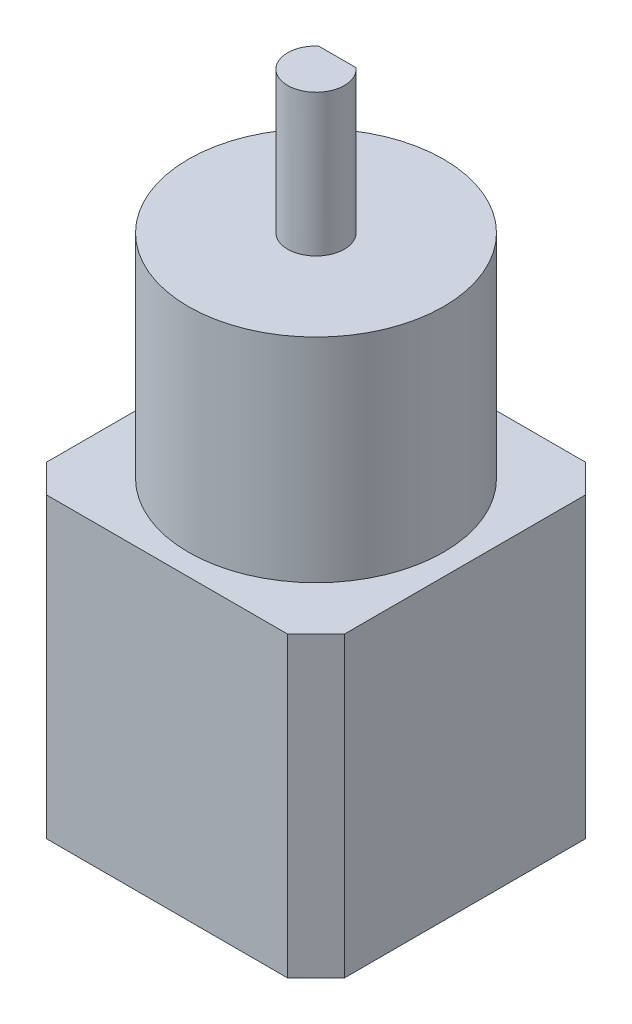
SolidWorks part; units mm, degrees
ref_plane "정면" through (0, 0, 0) normal (0, 0, 1) x (1, 0, 0)
ref_plane "윗면" through (0, 0, 0) normal (0, 1, 0) x (1, 0, 0)
ref_plane "우측면" through (0, 0, 0) normal (1, 0, 0) x (0, 0, -1)
sketch "스케치1" plane through (0, 0, 0) normal (0, 1, 0) x (1, 0, 0)
  line L1 (-21, -21) -> (21, -21)
  line L2 (-21, -21) -> (-21, 21)
  line L3 (-21, 21) -> (21, 21)
  line L4 (21, -21) -> (21, 21)
  line L5 (-21, -21) -> (21, 21) construction
  line L6 (-21, 21) -> (21, -21) construction
  point P0 (0, 0)
  dimension "D1" = 42
  dimension "D2" = 42
extrude "보스-돌출1" add sketch "스케치1" along normal mid plane 42
chamfer "모따기1" distance 4 angle 45 4 edges at (-21, 0, -21) (21, 0, -21) (-21, 0, 21) (21, 0, 21)
sketch "스케치2" plane through (0, 21, 0) normal (0, 1, 0) x (1, 0, 0)
  circle A0 centre (0, 0) radius 18
  dimension "D1" = 36
extrude "보스-돌출2" add sketch "스케치2" along normal blind 30
sketch "스케치3" plane through (0, 51, 0) normal (0, 1, 0) x (1, 0, 0)
  circle A0 centre (0, 0) radius 4
  dimension "D1" = 8
extrude "보스-돌출3" add sketch "스케치3" along normal blind 20
sketch "스케치4" plane through (0, 71, 0) normal (0, 1, 0) x (1, 0, 0)
  line L0 (-2.6458, 3) -> (2.6458, 3)
  line L1 (0, 3) -> (0, -4) construction
  circle A0 centre (0, 0) radius 4 construction
  circle A1 centre (0, 0) radius 4 construction
  arc A2 (-2.6458, 3) -> (2.6458, 3) centre (0, 0) cw
  dimension "D1" = 7
extrude "컷-돌출1" cut sketch "스케치4" against normal blind 15
